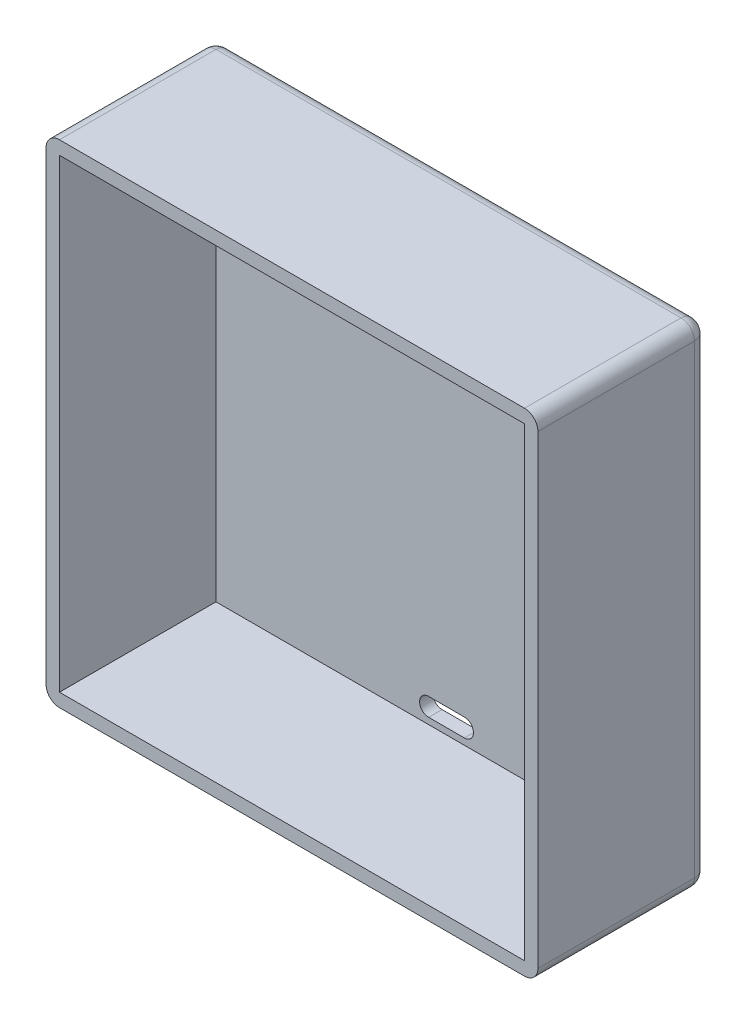
SolidWorks part; units mm, degrees
ref_plane "前视基准面" through (0, 0, 0) normal (0, 0, 1) x (1, 0, 0)
ref_plane "上视基准面" through (0, 0, 0) normal (0, 1, 0) x (1, 0, 0)
ref_plane "右视基准面" through (0, 0, 0) normal (1, 0, 0) x (0, 0, -1)
sketch "草图1" plane through (0, 0, 0) normal (0, 0, 1) x (1, 0, 0)
  line L1 (-55, 55) -> (55, 55)
  line L2 (-55, 55) -> (-55, -55)
  line L3 (-55, -55) -> (55, -55)
  line L4 (55, 55) -> (55, -55)
  line L5 (-55, 55) -> (55, -55) construction
  line L6 (-55, -55) -> (55, 55) construction
  line L7 (-52, 52) -> (52, 52)
  line L8 (-52, 52) -> (-52, -52)
  line L9 (-52, -52) -> (52, -52)
  line L10 (52, 52) -> (52, -52)
  line L11 (-52, 52) -> (52, -52) construction
  line L12 (-52, -52) -> (52, 52) construction
  point P0 (0, 0)
  point P5 (0, 0)
extrude "凸台-拉伸1" add sketch "草图1" along normal blind 38 contours L2 L3 L4 L1
sketch "草图3" plane through (0, 0, 38) normal (0, 0, 1) x (1, 0, 0)
  line L1 (-52, 52) -> (52, 52)
  line L2 (-52, 52) -> (-52, -52)
  line L3 (-52, -52) -> (52, -52)
  line L4 (52, 52) -> (52, -52)
  line L5 (-52, 52) -> (52, -52) construction
  line L6 (-52, -52) -> (52, 52) construction
  point P0 (0, 0)
extrude "切除-拉伸1" cut sketch "草图3" against normal blind 32
fillet "圆角1" radius 3 2 edges at (55, -55, 19) (55, 55, 19)
fillet "圆角2" radius 3 2 edges at (-55, -55, 19) (-55, 55, 19)
sketch "草图4" plane through (0, 0, 6) normal (0, 0, 1) x (1, 0, 0)
  line L0 (-3.9091, -48.5054) -> (3.9091, -48.5054) construction
  line L1 (-3.9091, -47.2554) -> (3.9091, -47.2554)
  line L2 (-3.9091, -49.7554) -> (3.9091, -49.7554)
  arc A0 (-3.9091, -47.2554) -> (-3.9091, -49.7554) centre (-3.9091, -48.5054) ccw
  arc A1 (3.9091, -49.7554) -> (3.9091, -47.2554) centre (3.9091, -48.5054) ccw
  point P2 (0, -48.5054)
extrude "切除-拉伸2" cut sketch "草图4" against normal through all
fillet "圆角3" radius 3 8 edges at (-54.1213, -54.1213, 0) (-54.1213, 54.1213, 0) (54.1213, 54.1213, 0) (54.1213, -54.1213, 0) (55, 0, 0) (0, 55, 0) (-55, 0, 0) (0, -55, 0)
sketch "草图7" plane through (0, 0, 0) normal (0, 0, -1) x (-1, 0, 0)
  line L0 (27.3516, -22.9618) -> (72.0452, -22.9618) construction
  line L1 (27.3516, -16.692) -> (72.0452, -16.692)
  line L2 (27.3516, -29.2316) -> (72.0452, -29.2316)
  line L3 (27.3893, -41.5563) -> (72.3829, -41.5563) construction
  line L4 (27.3893, -35.2866) -> (72.3829, -35.2866)
  line L5 (27.3893, -47.8261) -> (72.3829, -47.8261)
  line L6 (26.9498, -7.2387) -> (71.9435, -7.2387) construction
  line L7 (26.9498, -0.9689) -> (71.9435, -0.9689)
  line L8 (26.9498, -13.5084) -> (71.9435, -13.5084)
  line L9 (-74.8349, -22.9802) -> (-29.8412, -22.9802) construction
  line L10 (-74.8349, -16.7105) -> (-29.8412, -16.7105)
  line L11 (-74.8349, -29.25) -> (-29.8412, -29.25)
  line L12 (-74.4972, -41.5748) -> (-29.5035, -41.5748) construction
  line L13 (-74.4972, -35.305) -> (-29.5035, -35.305)
  line L14 (-74.4972, -47.8446) -> (-29.5035, -47.8446)
  line L15 (-74.9366, -7.2571) -> (-29.943, -7.2571) construction
  line L16 (-74.9366, -0.9873) -> (-29.943, -0.9873)
  line L17 (-74.9366, -13.5269) -> (-29.943, -13.5269)
  arc A0 (27.3516, -16.692) -> (27.3516, -29.2316) centre (27.3516, -22.9618) ccw
  arc A1 (72.0452, -29.2316) -> (72.0452, -16.692) centre (72.0452, -22.9618) ccw
  arc A2 (27.3893, -35.2866) -> (27.3893, -47.8261) centre (27.3893, -41.5563) ccw
  arc A3 (72.3829, -47.8261) -> (72.3829, -35.2866) centre (72.3829, -41.5563) ccw
  arc A4 (26.9498, -0.9689) -> (26.9498, -13.5084) centre (26.9498, -7.2387) ccw
  arc A5 (71.9435, -13.5084) -> (71.9435, -0.9689) centre (71.9435, -7.2387) ccw
  arc A6 (-74.8349, -16.7105) -> (-74.8349, -29.25) centre (-74.8349, -22.9802) ccw
  arc A7 (-29.8412, -29.25) -> (-29.8412, -16.7105) centre (-29.8412, -22.9802) ccw
  arc A8 (-74.4972, -35.305) -> (-74.4972, -47.8446) centre (-74.4972, -41.5748) ccw
  arc A9 (-29.5035, -47.8446) -> (-29.5035, -35.305) centre (-29.5035, -41.5748) ccw
  arc A10 (-74.9366, -0.9873) -> (-74.9366, -13.5269) centre (-74.9366, -7.2571) ccw
  arc A11 (-29.943, -13.5269) -> (-29.943, -0.9873) centre (-29.943, -7.2571) ccw
  point P3 (49.6984, -22.9618)
  point P10 (49.8861, -41.5563)
  point P17 (49.4466, -7.2387)
  point P24 (-52.338, -22.9802)
  point P31 (-52.0003, -41.5748)
  point P38 (-52.4398, -7.2571)
extrude "切除-拉伸4" cut sketch "草图7" against normal blind 1
sketch "草图10" plane through (0, 0, 0) normal (0, 0, -1) x (-1, 0, 0)
  line L0 (-3.5585, -48.5565) -> (4.4415, -48.5565) construction
  line L1 (-3.5585, -46.5315) -> (4.4415, -46.5315)
  line L2 (-3.5585, -50.5814) -> (4.4415, -50.5814)
  arc A0 (-2.5585, -47.5565) -> (-2.5585, -49.5565) centre (-2.5585, -48.5565) ccw construction
  arc A1 (3.4415, -49.5565) -> (3.4415, -47.5565) centre (3.4415, -48.5565) ccw construction
  arc A2 (-3.5585, -46.5315) -> (-3.5585, -50.5814) centre (-3.5585, -48.5565) ccw
  arc A3 (4.4415, -50.5814) -> (4.4415, -46.5315) centre (4.4415, -48.5565) ccw
  point P8 (0.4415, -48.5565)
extrude "切除-拉伸5" cut sketch "草图10" against normal blind 3
sketch "草图13" plane through (0, 0, 6) normal (0, 0, 1) x (1, 0, 0)
  line L1 (-52, 52) -> (52, 52)
  line L2 (-52, 52) -> (-52, -52)
  line L3 (-52, -52) -> (52, -52)
  line L4 (52, 52) -> (52, -52)
  line L5 (-52, 52) -> (52, -52) construction
  line L6 (-52, -52) -> (52, 52) construction
  point P0 (0, 0)
extrude "切除-拉伸6" cut sketch "草图13" against normal blind 3
